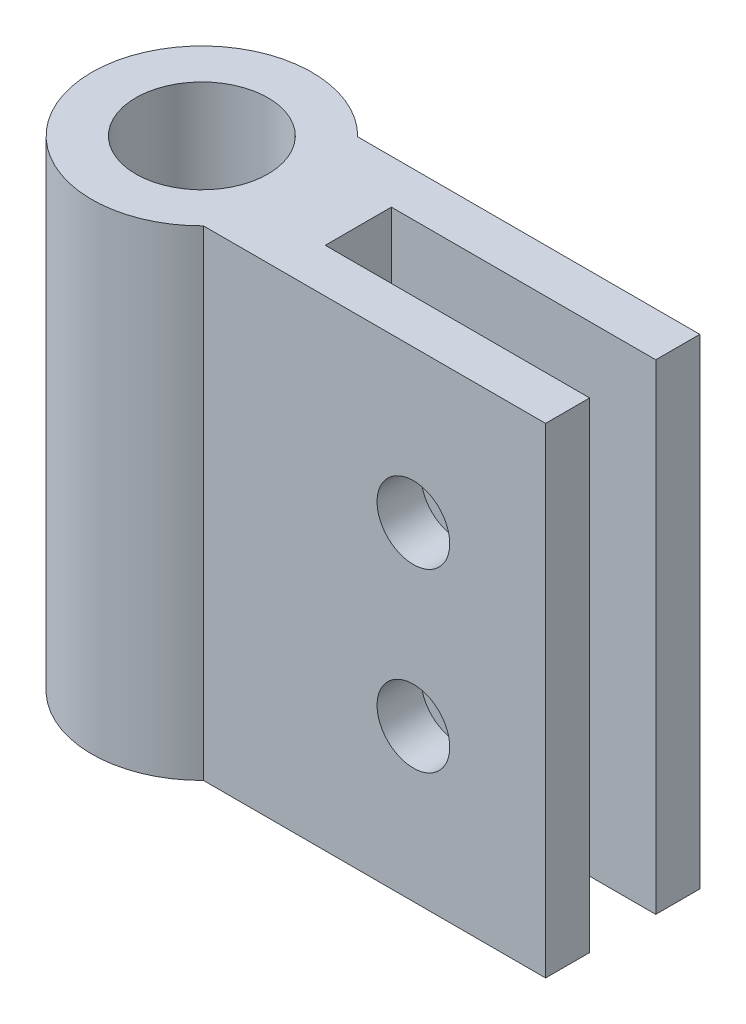
SolidWorks part; units mm, degrees
ref_plane "前视基准面" through (0, 0, 0) normal (0, 0, 1) x (1, 0, 0)
ref_plane "上视基准面" through (0, 0, 0) normal (0, 1, 0) x (1, 0, 0)
ref_plane "右视基准面" through (0, 0, 0) normal (1, 0, 0) x (0, 0, -1)
sketch "草图1" plane through (0, 0, 0) normal (0, 1, 0) x (1, 0, 0)
  circle A0 centre (0, 0) radius 3
  circle A1 centre (0, 0) radius 5
  dimension "D1" = 6
  dimension "D2" = 2
extrude "凸台-拉伸1" add sketch "草图1" along normal blind 21.8
sketch "草图2" plane through (0, 21.8, 0) normal (0, 1, 0) x (1, 0, 0)
  line L1 (19.1, -3.5) -> (3.1, -3.5)
  line L2 (19.1, -3.5) -> (19.1, 3.5)
  line L3 (19.1, 3.5) -> (3.1, 3.5)
  line L4 (3.1, -3.5) -> (3.1, 3.5)
  line L5 (19.1, -3.5) -> (3.1, 3.5) construction
  line L6 (19.1, 3.5) -> (3.1, -3.5) construction
  point P0 (11.1, 0)
  dimension "D1" = 11.1
  dimension "D2" = 16
  dimension "D3" = 7
extrude "凸台-拉伸2" add sketch "草图2" against normal up to surface (21.8 mm away) up to face at (0, 0, 5)
sketch "草图3" plane through (0, 21.8, 0) normal (0, 1, 0) x (1, 0, 0)
  line L0 (19.1, -3.5) -> (19.1, 3.5) construction
  line L1 (7.1, -1.5) -> (19.1, -1.5)
  line L2 (7.1, -1.5) -> (7.1, 1.5)
  line L3 (7.1, 1.5) -> (19.1, 1.5)
  line L4 (19.1, -1.5) -> (19.1, 1.5)
  line L5 (7.1, -1.5) -> (19.1, 1.5) construction
  line L6 (7.1, 1.5) -> (19.1, -1.5) construction
  point P0 (13.1, 0)
  dimension "D1" = 3
  dimension "D2" = 12
extrude "切除-拉伸1" cut sketch "草图3" against normal blind 22
sketch "草图4" plane through (0, 0, 3.5) normal (0, 0, 1) x (1, 0, 0)
  line L0 (7.1, 0) -> (7.1, 21.8) construction
  line L1 (7.1, 0) -> (7.1, 21.8) construction
  line L2 (3.5707, 21.8) -> (19.1, 21.8) construction
  circle A0 centre (13.1, 14.9) radius 1.65
  circle A1 centre (13.1, 6.9) radius 1.65
  dimension "D1" = 3.3
  dimension "D2" = 3.3
  dimension "D3" = 6.9
  dimension "D4" = 6
  dimension "D5" = 8
extrude "切除-拉伸2" cut sketch "草图4" against normal blind 22
